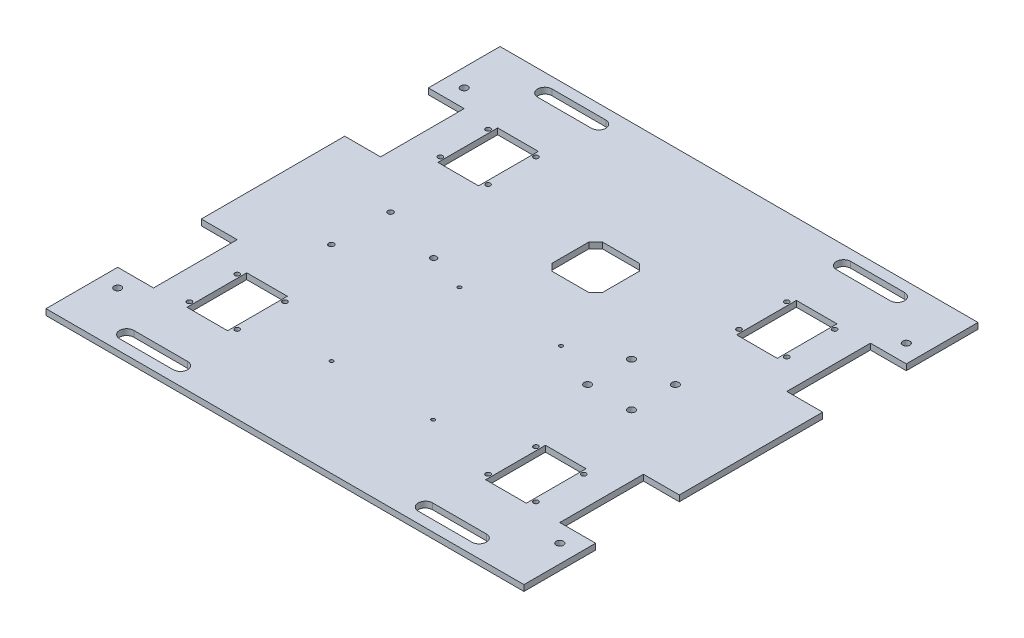
SolidWorks part; units mm, degrees
ref_plane "前基準面" through (0, 0, 0) normal (0, 0, 1) x (1, 0, 0)
ref_plane "上基準面" through (0, 0, 0) normal (0, 1, 0) x (1, 0, 0)
ref_plane "右基準面" through (0, 0, 0) normal (1, 0, 0) x (0, 0, -1)
sketch "草圖1" plane through (0, 0, 0) normal (0, 1, 0) x (1, 0, 0)
  line L0 (200, 190) -> (200, -190)
  line L1 (200, 190) -> (-200, 190)
  line L3 (200, -190) -> (-200, -190)
  line L4 (-200, 190) -> (-200, -190)
  line L5 (0, -190) -> (0, 190) construction
  line L6 (200, 0) -> (-200, 0) construction
  line L8 (-200, 130) -> (-200, -130) construction
  line L10 (-170, 130) -> (-170, -130) construction
  line L11 (-200, 130) -> (200, 130) construction
  line L12 (-200, 130) -> (-200, 190) construction
  line L13 (-200, 190) -> (200, 190) construction
  line L15 (-200, -130) -> (200, -130) construction
  line L16 (-200, -130) -> (-200, -190) construction
  line L17 (-200, -190) -> (200, -190) construction
  line L19 (170, 130) -> (170, -130) construction
  point P0 (0, 0)
  dimension "D1" = 400
  dimension "D2" = 260
  dimension "D3" = 60
  dimension "D4" = 60
  dimension "D5" = 30
extrude "填料-伸長1" add sketch "草圖1" along normal blind 5
sketch "草圖2" plane through (0, 5, 0) normal (0, 1, 0) x (1, 0, 0)
  line L0 (200, -190) -> (200, 190) construction
  line L1 (-200, 190) -> (200, 190) construction
  line L5 (-185, 190) -> (-185, -190) construction
  line L21 (-200, 190) -> (200, 190) construction
  line L22 (-200, 190) -> (-200, 130) construction
  line L23 (-200, 130) -> (200, 130) construction
  line L24 (-275.3304, 0) -> (275.3304, 0) construction
  line L25 (0, 247.3454) -> (0, -229.8147) construction
  line L42 (200, 190) -> (200, 130) construction
  line L44 (-155, 35) -> (-72.5, 35) construction
  line L45 (-155, 35) -> (-155, -35) construction
  line L46 (-155, -35) -> (-72.5, -35) construction
  line L47 (-72.5, 35) -> (-72.5, -35) construction
  line L59 (-200, 160) -> (200, 160) construction
  line L60 (-200, 145) -> (200, 145) construction
  line L61 (-200, -145) -> (200, -145) construction
  line L62 (-200, -160) -> (200, -160) construction
  line L63 (-200, -130) -> (200, -130) construction
  line L64 (200, -190) -> (200, -130) construction
  line L65 (-200, -190) -> (200, -190) construction
  line L66 (-200, -190) -> (-200, -130) construction
  line L67 (185, -190) -> (185, 190) construction
  line L68 (-200, 130) -> (-170, 130) construction
  line L69 (-200, 130) -> (-200, -130) construction
  line L70 (-200, -130) -> (-170, -130) construction
  line L71 (-170, 130) -> (-170, -130) construction
  line L72 (200, 130) -> (170, 130) construction
  line L73 (200, 130) -> (200, -130) construction
  line L74 (200, -130) -> (170, -130) construction
  line L75 (170, 130) -> (170, -130) construction
  line L76 (170, -60) -> (200, -60)
  line L77 (-200, 130) -> (-170, 130)
  line L78 (-200, 130) -> (-200, 60)
  line L79 (-200, 60) -> (-170, 60)
  line L80 (-170, 130) -> (-170, 60)
  line L81 (-170, -130) -> (-200, -130)
  line L82 (-170, -130) -> (-170, -60)
  line L83 (-170, -60) -> (-200, -60)
  line L84 (-200, -130) -> (-200, -60)
  line L85 (200, -130) -> (200, -60)
  line L86 (170, -130) -> (200, -130)
  line L87 (170, -130) -> (170, -60)
  line L88 (200, 60) -> (170, 60)
  line L89 (170, 130) -> (170, 60)
  line L90 (200, 130) -> (170, 130)
  line L91 (200, 130) -> (200, 60)
  line L100 (100, -80) -> (150, -80) construction
  line L101 (78.65, 21.35) -> (121.35, 21.35) construction
  line L102 (78.65, 21.35) -> (78.65, -21.35) construction
  line L103 (78.65, -21.35) -> (121.35, -21.35) construction
  line L104 (121.35, 21.35) -> (121.35, -21.35) construction
  line L105 (-150, -80) -> (-100, -80) construction
  line L106 (-150, -80) -> (-150, -130) construction
  line L107 (-150, -130) -> (-100, -130) construction
  line L108 (-100, -80) -> (-100, -130) construction
  line L109 (-142, -80) -> (-108, -80)
  line L110 (-142, -80) -> (-142, -130)
  line L111 (-142, -130) -> (-108, -130)
  line L112 (-108, -80) -> (-108, -130)
  line L113 (100, -80) -> (100, -130) construction
  line L114 (100, -130) -> (150, -130) construction
  line L115 (150, -80) -> (150, -130) construction
  line L116 (108, -80) -> (142, -80)
  line L117 (108, -80) -> (108, -130)
  line L118 (108, -130) -> (142, -130)
  line L119 (142, -80) -> (142, -130)
  line L120 (-150, 130) -> (-100, 130) construction
  line L121 (-150, 130) -> (-150, 80) construction
  line L122 (-150, 80) -> (-100, 80) construction
  line L123 (-100, 130) -> (-100, 80) construction
  line L124 (-142, 130) -> (-108, 130)
  line L125 (-142, 130) -> (-142, 80)
  line L126 (-142, 80) -> (-108, 80)
  line L127 (-108, 130) -> (-108, 80)
  line L128 (100, 130) -> (150, 130) construction
  line L129 (100, 130) -> (100, 80) construction
  line L130 (100, 80) -> (150, 80) construction
  line L131 (150, 130) -> (150, 80) construction
  line L132 (108, 130) -> (142, 130)
  line L133 (108, 130) -> (108, 80)
  line L134 (108, 80) -> (142, 80)
  line L135 (142, 130) -> (142, 80)
  line L136 (-21.15, 85.5) -> (-15.5, 91.15)
  line L137 (44, -110) -> (-44, -110) construction
  line L138 (44, -110) -> (44, 0) construction
  line L139 (44, 0) -> (-44, 0) construction
  line L140 (-44, -110) -> (-44, 0) construction
  line L141 (-15.5, 91.15) -> (15.5, 91.15)
  line L142 (-21.15, 85.5) -> (-21.15, 54.5)
  line L143 (-15.5, 48.85) -> (15.5, 48.85)
  line L144 (21.15, 85.5) -> (21.15, 54.5)
  line L145 (15.5, 91.15) -> (21.15, 85.5)
  line L146 (15.5, 48.85) -> (21.15, 54.5)
  line L147 (-21.15, 54.5) -> (-15.5, 48.85)
  line L148 (-234.8869, -145) -> (-234.8869, -175) construction
  line L149 (-214.8869, -145) -> (-214.8869, -175)
  line L150 (-254.8869, -145) -> (-254.8869, -175)
  line L151 (-234.8869, 145) -> (-234.8869, 175) construction
  line L152 (-214.8869, 145) -> (-214.8869, 175)
  line L153 (-254.8869, 145) -> (-254.8869, 175)
  line L154 (234.8869, -145) -> (234.8869, -175) construction
  line L155 (214.8869, -145) -> (214.8869, -175)
  line L156 (254.8869, -145) -> (254.8869, -175)
  line L157 (234.8869, 145) -> (234.8869, 175) construction
  line L158 (214.8869, 145) -> (214.8869, 175)
  line L159 (254.8869, 145) -> (254.8869, 175)
  line L160 (-147.5, 175) -> (-102.5, 175) construction
  line L161 (-147.5, 181) -> (-102.5, 181)
  line L162 (-147.5, 169) -> (-102.5, 169)
  line L163 (-147.5, -175) -> (-102.5, -175) construction
  line L164 (-147.5, -181) -> (-102.5, -181)
  line L165 (-147.5, -169) -> (-102.5, -169)
  line L166 (147.5, 175) -> (102.5, 175) construction
  line L167 (147.5, 181) -> (102.5, 181)
  line L168 (147.5, 169) -> (102.5, 169)
  line L169 (147.5, -175) -> (102.5, -175) construction
  line L170 (147.5, -181) -> (102.5, -181)
  line L171 (147.5, -169) -> (102.5, -169)
  circle A21 centre (-127.07, -24.13) radius 2.25
  circle A22 centre (-125.8, 24.13) radius 2.25
  circle A23 centre (-74.5, 8.89) radius 2.5
  circle A32 centre (-185, 145) radius 3
  circle A33 centre (185, 145) radius 3
  circle A34 centre (-185, -145) radius 3
  circle A35 centre (185, -145) radius 3
  circle A40 centre (81.65, 18.35) radius 3
  circle A41 centre (118.35, 18.35) radius 3
  circle A42 centre (81.65, -18.35) radius 3
  circle A43 centre (118.35, -18.35) radius 3
  circle A44 centre (-145, -85) radius 2
  circle A45 centre (-105, -85) radius 2
  circle A46 centre (-145, -125) radius 2
  circle A47 centre (-105, -125) radius 2
  circle A48 centre (105, -85) radius 2
  circle A49 centre (145, -85) radius 2
  circle A50 centre (105, -125) radius 2
  circle A51 centre (145, -125) radius 2
  circle A52 centre (-145, 125) radius 2
  circle A53 centre (-105, 125) radius 2
  circle A54 centre (-145, 85) radius 2
  circle A55 centre (-105, 85) radius 2
  circle A56 centre (105, 125) radius 2
  circle A57 centre (145, 125) radius 2
  circle A58 centre (105, 85) radius 2
  circle A59 centre (145, 85) radius 2
  circle A60 centre (-42.5, -1.5) radius 1.5
  circle A61 centre (42.5, -1.5) radius 1.5
  circle A62 centre (-42.5, -108.5) radius 1.5
  circle A63 centre (42.5, -108.5) radius 1.5
  circle A64 centre (-15.5, 85.5) radius 1.5 construction
  circle A65 centre (15.5, 85.5) radius 1.5 construction
  circle A66 centre (-15.5, 54.5) radius 1.5 construction
  circle A67 centre (15.5, 54.5) radius 1.5 construction
  arc A68 (-214.8869, -145) -> (-254.8869, -145) centre (-234.8869, -145) ccw
  arc A69 (-254.8869, -175) -> (-214.8869, -175) centre (-234.8869, -175) ccw
  arc A70 (-214.8869, 145) -> (-254.8869, 145) centre (-234.8869, 145) cw
  arc A71 (-254.8869, 175) -> (-214.8869, 175) centre (-234.8869, 175) cw
  arc A72 (214.8869, -145) -> (254.8869, -145) centre (234.8869, -145) cw
  arc A73 (254.8869, -175) -> (214.8869, -175) centre (234.8869, -175) cw
  arc A74 (214.8869, 145) -> (254.8869, 145) centre (234.8869, 145) ccw
  arc A75 (254.8869, 175) -> (214.8869, 175) centre (234.8869, 175) ccw
  arc A76 (-147.5, 181) -> (-147.5, 169) centre (-147.5, 175) ccw
  arc A77 (-102.5, 169) -> (-102.5, 181) centre (-102.5, 175) ccw
  arc A78 (-147.5, -181) -> (-147.5, -169) centre (-147.5, -175) cw
  arc A79 (-102.5, -169) -> (-102.5, -181) centre (-102.5, -175) cw
  arc A80 (147.5, 181) -> (147.5, 169) centre (147.5, 175) cw
  arc A81 (102.5, 169) -> (102.5, 181) centre (102.5, 175) cw
  arc A82 (147.5, -181) -> (147.5, -169) centre (147.5, -175) ccw
  arc A83 (102.5, -169) -> (102.5, -181) centre (102.5, -175) ccw
  point P54 (0, 70)
  point P55 (0, 91.15)
  point P56 (-234.8869, -160)
  point P62 (-113.75, 0)
  point P64 (-155, 0)
  point P70 (-234.8869, -125)
  point P71 (-234.8869, -195)
  point P73 (-125, 175)
  point P89 (-234.8869, 160)
  point P102 (-113.75, 35)
  point P175 (0, 0)
  point P177 (-44, -55)
  point P182 (0, -55)
  point P183 (100, 21.35)
  point P185 (78.65, 0)
  point P187 (234.8869, -160)
  point P191 (100, 0)
  point P195 (234.8869, 160)
  point P203 (125, 175)
  point P204 (-21.15, 91.15)
  point P205 (21.15, 48.85)
  point P206 (-21.15, 48.85)
  point P207 (21.15, 91.15)
  point P224 (-21.15, 70)
  point P227 (-125, -175)
  point P235 (0, 0)
  point P238 (125, -175)
  dimension "D5" = 60
  dimension "D6" = 15
  dimension "D7" = 30
  dimension "D9" = 6
  dimension "D18" = 4.5
  dimension "D25" = 5
  dimension "D28" = 42.7
  dimension "D35" = 125
  dimension "D10" = 6
  dimension "D13" = 70
  dimension "D30" = 6
  dimension "D31" = 50
  dimension "D32" = 50
  dimension "D33" = 40
  dimension "D37" = 4
  dimension "D46" = 4
  dimension "D55" = 4
  dimension "D64" = 4
  dimension "D73" = 3
  dimension "D77" = 3
  dimension "D26" = 6
  dimension "D92" = 6
  dimension "D3" = 15
  dimension "D4" = 15
  dimension "D11" = 70
  dimension "D12" = 40
  dimension "D14" = 120
  dimension "D15" = 200
  dimension "D16" = 82.5
  dimension "D17" = 70
  dimension "D19" = 10.87
  dimension "D20" = 27.93
  dimension "D21" = 29.2
  dimension "D22" = 10.87
  dimension "D23" = 26.11
  dimension "D24" = 2
  dimension "D27" = 15
  dimension "D29" = 42.7
  dimension "D34" = 45
  dimension "D36" = 40
  dimension "D38" = 5
  dimension "D90" = 45
  dimension "D39" = 5
  dimension "D40" = 34
  dimension "D41" = 8
  dimension "D42" = 50
  dimension "D43" = 50
  dimension "D44" = 40
  dimension "D45" = 40
  dimension "D47" = 5
  dimension "D48" = 5
  dimension "D49" = 34
  dimension "D50" = 8
  dimension "D51" = 50
  dimension "D52" = 50
  dimension "D53" = 40
  dimension "D54" = 40
  dimension "D56" = 5
  dimension "D57" = 5
  dimension "D58" = 34
  dimension "D59" = 8
  dimension "D60" = 50
  dimension "D61" = 50
  dimension "D62" = 40
  dimension "D63" = 40
  dimension "D65" = 5
  dimension "D66" = 5
  dimension "D67" = 34
  dimension "D68" = 8
  dimension "D69" = 20
  dimension "D70" = 20
  dimension "D71" = 88
  dimension "D72" = 110
  dimension "D74" = 15
  dimension "D75" = 42.3
  dimension "D76" = 42.3
  dimension "D78" = 31
  dimension "D79" = 31
  dimension "D80" = 5.65
  dimension "D81" = 5.65
  dimension "D82" = 5.65
  dimension "D83" = 5.65
  dimension "D84" = 5.65
  dimension "D85" = 5.65
  dimension "D86" = 5.65
  dimension "D87" = 5.65
  dimension "D88" = 5.65
  dimension "D89" = 5.65
  dimension "D91" = 125
  dimension "D93" = 15
extrude "除料-伸長1" cut sketch "草圖2" against normal through all
ref_plane "平面1" through (-200, 5, -60) normal (0, 0, 1) x (1, 0, 0)
